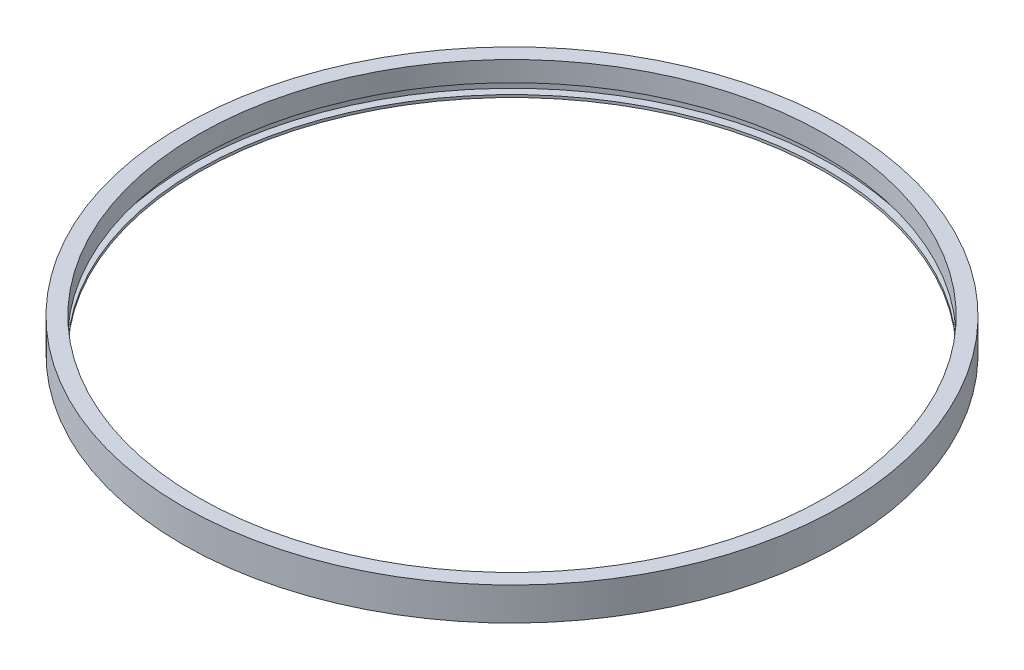
SolidWorks part; units mm, degrees
material "AISI 1020"
ref_plane "Alzado" through (0, 0, 0) normal (0, 0, 1) x (1, 0, 0)
ref_plane "Planta" through (0, 0, 0) normal (0, 1, 0) x (1, 0, 0)
ref_plane "Vista lateral" through (0, 0, 0) normal (1, 0, 0) x (0, 0, -1)
sketch "Croquis1" plane through (0, 0, 0) normal (0, 1, 0) x (1, 0, 0)
  circle A0 centre (0, 0) radius 61
  circle A1 centre (0, 0) radius 64
  dimension "D1" = 122
  dimension "D2" = 128
extrude "Saliente-Extruir1" add sketch "Croquis1" along normal blind 3.9
sketch "Croquis2" plane through (0, 0, 0) normal (0, -1, 0) x (1, 0, 0)
  circle A0 centre (0, 0) radius 64
  circle A1 centre (0, 0) radius 62.5
  dimension "D1" = 128
  dimension "D2" = 125
extrude "Saliente-Extruir2" add sketch "Croquis2" along normal blind 2
sketch "Croquis3" plane through (0, -2, 0) normal (0, -1, 0) x (1, 0, 0)
  circle A0 centre (0, 0) radius 64
  circle A1 centre (0, 0) radius 61
  dimension "D1" = 128
  dimension "D2" = 122
extrude "Saliente-Extruir3" add sketch "Croquis3" along normal blind 0.5
sketch "Croquis4" plane through (-70.182, -108.3617, -25.3143) normal (-0.3393, 0, 0.9407) x (0.9407, 0, 0.3393)
  line L0 (65.1739, 112.2617) -> (65.1739, 105.8617) construction
  line L1 (138.6078, 112.2617) -> (10.6078, 112.2617) construction
  line L2 (10.6078, 105.8617) -> (138.6078, 105.8617) construction
